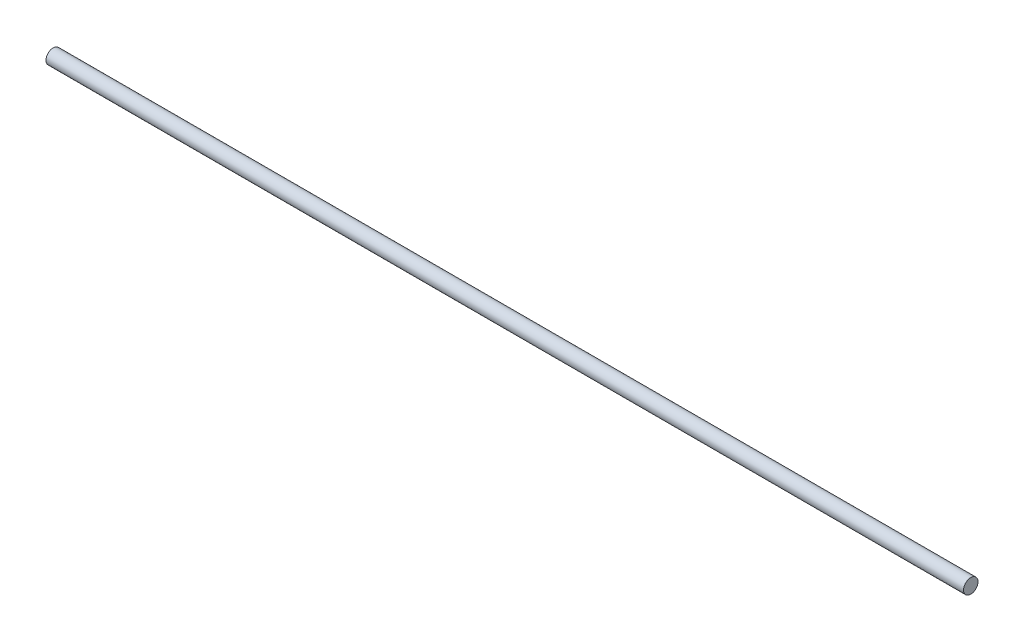
SolidWorks part; units mm, degrees
ref_plane "Front Plane" through (0, 0, 0) normal (0, 0, 1) x (1, 0, 0)
ref_plane "Top Plane" through (0, 0, 0) normal (0, 1, 0) x (1, 0, 0)
ref_plane "Right Plane" through (0, 0, 0) normal (1, 0, 0) x (0, 0, -1)
sketch "Sketch1" plane through (0, 0, 0) normal (1, 0, 0) x (0, 0, -1)
  circle A0 centre (0, 0) radius 6
extrude "Boss-Extrude1" add sketch "Sketch1" along normal mid plane 762
